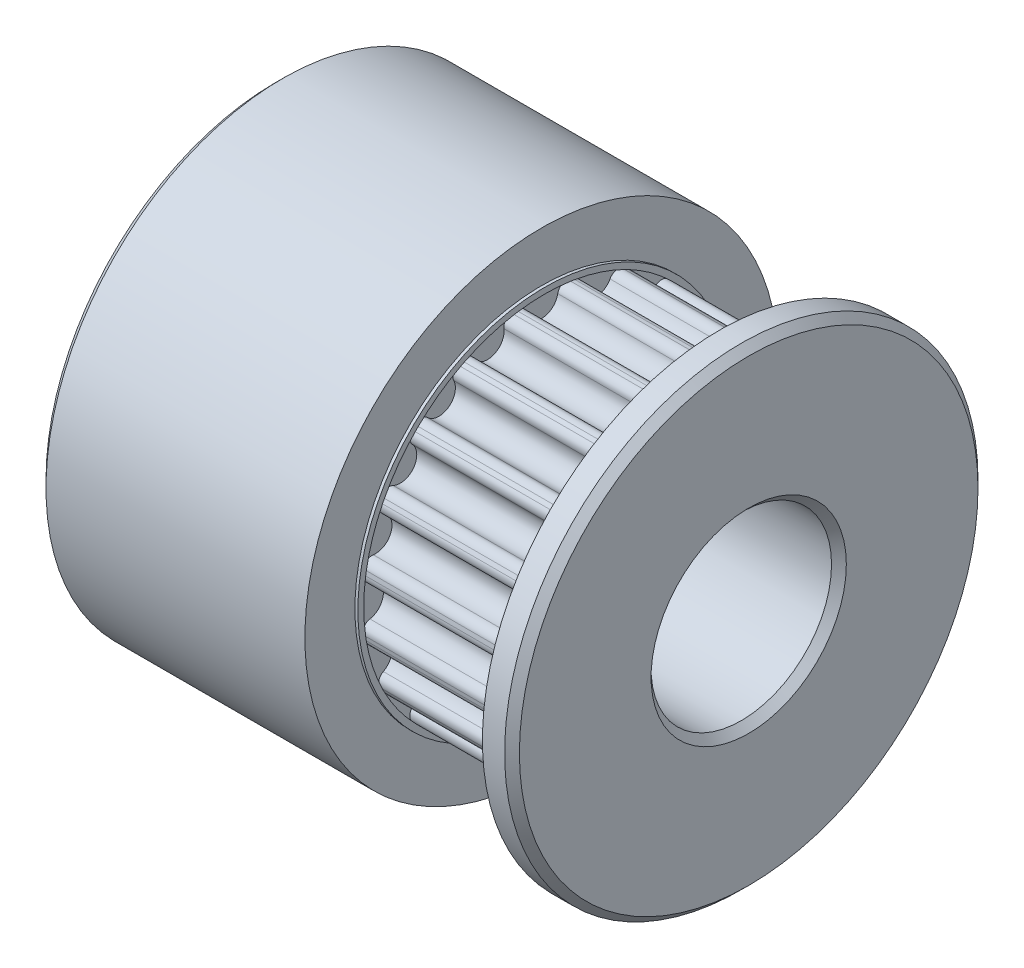
SolidWorks part; units mm, degrees
ref_plane "Front Plane" through (0, 0, 0) normal (0, 0, 1) x (1, 0, 0)
ref_plane "Top Plane" through (0, 0, 0) normal (0, 1, 0) x (1, 0, 0)
ref_plane "Right Plane" through (0, 0, 0) normal (1, 0, 0) x (0, 0, -1)
sketch "Sketch1" plane through (0, 0, 0) normal (1, 0, 0) x (0, 0, -1)
  line L0 (-8.0027, 0.002) -> (7.9973, 0.002) construction
  line L1 (-0.5912, -5.3455) -> (0.627, -5.3455) construction
  line L2 (0, 0) -> (0, -10.4547) construction
  line L3 (-0.6734, -6.11) -> (-0.514, -6.11) construction
  line L4 (0.514, -6.11) -> (0.627, -6.11) construction
  circle A0 centre (0, 0) radius 8 construction
  arc A1 (0.5225, -6.0876) -> (1.3842, -5.9511) centre (0, 0) ccw
  arc A2 (0.5225, -6.0876) -> (-0.5225, -6.0876) centre (0, -5.9005) ccw
  arc A3 (-1.3842, -5.9511) -> (-2.3781, -5.6282) centre (-1.8234, -5.6117) ccw
  arc A4 (-3.1555, -5.2321) -> (-4.0009, -4.6179) centre (-3.4682, -4.7736) ccw
  arc A5 (-4.6179, -4.0009) -> (-5.2321, -3.1555) centre (-4.7736, -3.4682) ccw
  arc A6 (-5.6282, -2.3781) -> (-5.9511, -1.3842) centre (-5.6117, -1.8234) ccw
  arc A7 (-6.0876, -0.5225) -> (-6.0876, 0.5225) centre (-5.9005, 0) ccw
  arc A8 (-5.9511, 1.3842) -> (-5.6282, 2.3781) centre (-5.6117, 1.8234) ccw
  arc A9 (-5.2321, 3.1555) -> (-4.6179, 4.0009) centre (-4.7736, 3.4682) ccw
  arc A10 (-4.0009, 4.6179) -> (-3.1555, 5.2321) centre (-3.4682, 4.7736) ccw
  arc A11 (-2.3781, 5.6282) -> (-1.3842, 5.9511) centre (-1.8234, 5.6117) ccw
  arc A12 (-0.5225, 6.0876) -> (0.5225, 6.0876) centre (0, 5.9005) ccw
  arc A13 (1.3842, 5.9511) -> (2.3781, 5.6282) centre (1.8234, 5.6117) ccw
  arc A14 (3.1555, 5.2321) -> (4.0009, 4.6179) centre (3.4682, 4.7736) ccw
  arc A15 (4.6179, 4.0009) -> (5.2321, 3.1555) centre (4.7736, 3.4682) ccw
  arc A16 (5.6282, 2.3781) -> (5.9511, 1.3842) centre (5.6117, 1.8234) ccw
  arc A17 (6.0876, 0.5225) -> (6.0876, -0.5225) centre (5.9005, 0) ccw
  arc A18 (5.9511, -1.3842) -> (5.6282, -2.3781) centre (5.6117, -1.8234) ccw
  arc A19 (5.2321, -3.1555) -> (4.6179, -4.0009) centre (4.7736, -3.4682) ccw
  arc A20 (4.0009, -4.6179) -> (3.1555, -5.2321) centre (3.4682, -4.7736) ccw
  arc A21 (2.3781, -5.6282) -> (1.3842, -5.9511) centre (1.8234, -5.6117) ccw
  arc A22 (-1.3842, -5.9511) -> (-0.5225, -6.0876) centre (0, 0) ccw
  arc A23 (-3.1555, -5.2321) -> (-2.3781, -5.6282) centre (0, 0) ccw
  arc A24 (2.3781, -5.6282) -> (3.1555, -5.2321) centre (0, 0) ccw
  arc A25 (4.0009, -4.6179) -> (4.6179, -4.0009) centre (0, 0) ccw
  arc A26 (5.2321, -3.1555) -> (5.6282, -2.3781) centre (0, 0) ccw
  arc A27 (5.9511, -1.3842) -> (6.0876, -0.5225) centre (0, 0) ccw
  arc A28 (6.0876, 0.5225) -> (5.9511, 1.3842) centre (0, 0) ccw
  arc A29 (5.6282, 2.3781) -> (5.2321, 3.1555) centre (0, 0) ccw
  arc A30 (4.6179, 4.0009) -> (4.0009, 4.6179) centre (0, 0) ccw
  arc A31 (3.1555, 5.2321) -> (2.3781, 5.6282) centre (0, 0) ccw
  arc A32 (1.3842, 5.9511) -> (0.5225, 6.0876) centre (0, 0) ccw
  arc A33 (-0.5225, 6.0876) -> (-1.3842, 5.9511) centre (0, 0) ccw
  arc A34 (-2.3781, 5.6282) -> (-3.1555, 5.2321) centre (0, 0) ccw
  arc A35 (-4.0009, 4.6179) -> (-4.6179, 4.0009) centre (0, 0) ccw
  arc A36 (-5.2321, 3.1555) -> (-5.6282, 2.3781) centre (0, 0) ccw
  arc A37 (-5.9511, 1.3842) -> (-6.0876, 0.5225) centre (0, 0) ccw
  arc A38 (-6.0876, -0.5225) -> (-5.9511, -1.3842) centre (0, 0) ccw
  arc A39 (-5.6282, -2.3781) -> (-5.2321, -3.1555) centre (0, 0) ccw
  arc A40 (-4.6179, -4.0009) -> (-4.0009, -4.6179) centre (0, 0) ccw
  point P74 (0, 0)
  dimension "D2" = 16
  dimension "D3" = 12.22
  dimension "D4" = 1.11
  dimension "D1" = 16
  dimension "D5" = 20
extrude "Boss-Extrude1" add sketch "Sketch1" along normal blind 6
fillet "Fillet1" radius 0.3 40 edges at (3, -0.5225, 6.0876) (3, -2.3781, 5.6282) (3, -4.0009, 4.6179) (3, -5.2321, 3.1555) (3, -5.9511, 1.3842) (3, -6.0876, -0.5225) (3, -5.6282, -2.3781) (3, -4.6179, -4.0009) (3, -3.1555, -5.2321) (3, -1.3842, -5.9511) (3, 0.5225, -6.0876) (3, 2.3781, -5.6282) (3, 4.0009, -4.6179) (3, 5.2321, -3.1555) (3, 5.9511, -1.3842) (3, 5.6282, 2.3781) (3, 4.6179, 4.0009) (3, 3.1555, 5.2321) (3, 1.3842, 5.9511) (3, 2.3781, 5.6282) (3, 0.5225, 6.0876) (3, -1.3842, 5.9511) (3, -3.1555, 5.2321) (3, -4.6179, 4.0009) (3, -5.6282, 2.3781) (3, -6.0876, 0.5225) (3, -5.9511, -1.3842) (3, -5.2321, -3.1555) (3, -4.0009, -4.6179) (3, -2.3781, -5.6282) (3, -0.5225, -6.0876) (3, 1.3842, -5.9511) (3, 3.1555, -5.2321) (3, 4.6179, -4.0009) (3, 5.6282, -2.3781) (3, 6.0876, -0.5225) (3, 5.9511, 1.3842) (3, 5.2321, 3.1555) (3, 4.0009, 4.6179) (3, 6.0876, 0.5225)
sketch "Sketch2" plane through (0, 0, 0) normal (1, 0, 0) x (0, 0, -1)
  circle A0 centre (0, 0) radius 8
  dimension "D1" = 16
extrude "Boss-Extrude2" add sketch "Sketch2" against normal blind 9
sketch "Sketch3" plane through (6, 0, 0) normal (1, 0, 0) x (0, 0, -1)
  circle A0 centre (0, 0) radius 8 construction
  circle A1 centre (0, 0) radius 8
extrude "Boss-Extrude3" add sketch "Sketch3" along normal blind 1
sketch "Sketch4" plane through (0, 0, 0) normal (1, 0, 0) x (0, 0, -1)
  circle A0 centre (0, 0) radius 3.05
  dimension "D1" = 6.1
extrude "Cut-Extrude1" cut sketch "Sketch4" against normal through all both and the other way through all
chamfer "Chamfer1" distance 0.25 angle 45 4 edges at (-9, 0, -8) (-9, 0, -3.05) (7, 0, -8) (7, 0, -3.05)
sketch "Sketch5" plane through (0, 0, 0) normal (0, 0, 1) x (1, 0, 0)
  line L0 (-9, 7.75) -> (-9, -7.75) construction
  circle A0 centre (-5, 0) radius 1.75
  dimension "D1" = 3.5
  dimension "D2" = 4
extrude "Cut-Extrude2" cut sketch "Sketch5" against normal through all
ref_plane "Plane2" through (-8.75, 0, 0) normal (1, 0, 0) x (0, 0, -1)
sketch "Sketch8" plane through (-8.75, 0, 0) normal (1, 0, 0) x (0, 0, -1)
  line L0 (-2.227, 3.05) -> (2.6592, 3.05) construction
  line L1 (-1.7471, -2.5) -> (1.7471, -2.5)
  circle A0 centre (0, 0) radius 3.05 construction
  arc A1 (-1.7471, -2.5) -> (1.7471, -2.5) centre (0, 0) ccw
  dimension "D1" = 5.55
sketch "Sketch6" plane through (0, 0, 0) normal (0, 1, 0) x (1, 0, 0)
  line L0 (-9, 7.75) -> (-9, -7.75) construction
  circle A0 centre (-5, 0) radius 1.75
  dimension "D1" = 3.5
  dimension "D2" = 4
extrude "Cut-Extrude3" cut sketch "Sketch6" against normal through all
ref_plane "Plane3" through (0, -10, 0) normal (0, 1, 0) x (1, 0, 0)
sketch "Sketch9" plane through (0, -10, 0) normal (0, 1, 0) x (1, 0, 0)
  circle A0 centre (-5, 0) radius 1.75 construction
  circle A1 centre (-5, 0) radius 1.75
ref_plane "Plane4" through (-5, 0, 0) normal (-1, 0, 0) x (0, 0, 1)
sketch "Sketch10" plane through (-5, 0, 0) normal (-1, 0, 0) x (0, 0, 1)
  line L0 (0, -10) -> (0, 0) construction
  line L1 (1.75, -10) -> (-1.75, -10) construction
sketch "Sketch11" plane through (7, 0, 0) normal (1, 0, 0) x (0, 0, -1)
  circle A0 centre (0, 0) radius 6.11 construction
  dimension "D1" = 12.22
sketch "Sketch12" plane through (0, 0, 0) normal (1, 0, 0) x (0, 0, -1)
  circle A0 centre (0, 0) radius 6.11
  circle A1 centre (0, 0) radius 6.31
  dimension "D1" = 0.2
extrude "Boss-Extrude4" add sketch "Sketch12" along normal blind 0.1
